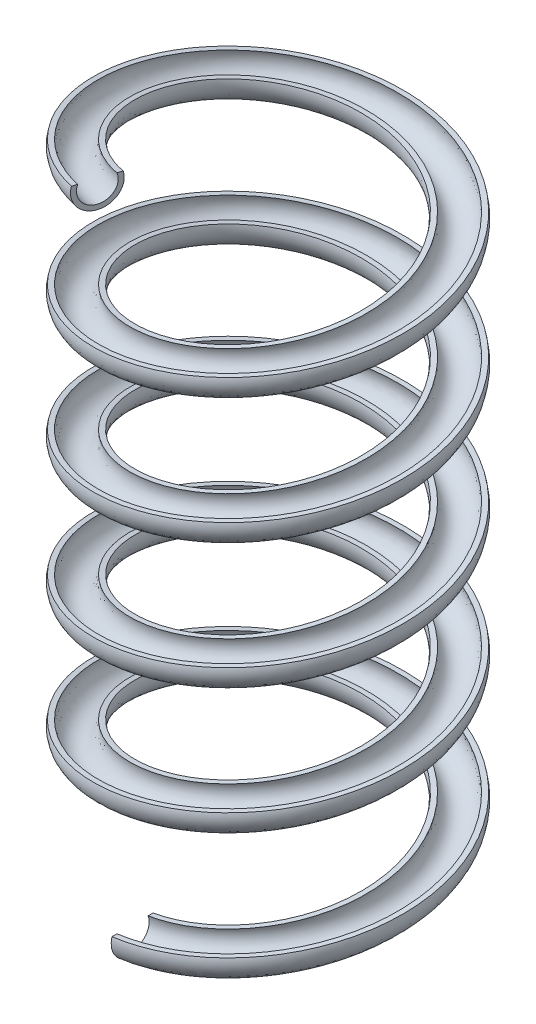
SolidWorks part; units mm, degrees
material "Custom Plastic"
ref_plane "Front Plane" through (0, 0, 0) normal (0, 0, 1) x (1, 0, 0)
ref_plane "Top Plane" through (0, 0, 0) normal (0, 1, 0) x (1, 0, 0)
ref_plane "Right Plane" through (0, 0, 0) normal (1, 0, 0) x (0, 0, -1)
sketch "Sketch2" plane through (0, 0, 0) normal (0, 1, 0) x (1, 0, 0)
  circle A0 centre (0, 0) radius 171.45
  dimension "D1" = 342.9
curve "Helix/Spiral2" pitch 159.0707 height 787.4 turns 4.95
ref_plane "Plane5" through (0, 0, 0) normal (1, 0, 0) x (0, 0, -1)
sketch "Sketch6" plane through (0, 0, 0) normal (1, 0, 0) x (0, 0, -1)
  line L0 (-151.765, 7.1842) -> (-145.415, 7.1842)
  line L1 (-191.135, 7.1842) -> (-197.485, 7.1842)
  arc A0 (-191.135, 7.1842) -> (-151.765, 7.1842) centre (-171.45, 0) ccw
  arc A1 (-145.415, 7.1842) -> (-197.485, 7.1842) centre (-171.45, 0) cw
  spline S0 degree 3 poles (-171.45, 0) (-171.45, 0.9078) (-170.7875, 2.7248) (-167.8175, 5.4491) (-162.9059, 8.1737) (-156.1093, 10.8983) (-147.5065, 13.6228) (-137.1969, 16.3474) (-125.2998, 19.072) (-111.953, 21.7965) (-97.3108, 24.5211) (-81.5427, 27.2457) (-64.831, 29.9702) (-47.3693, 32.6948) (-29.3594, 35.4194) (-11.0099, 38.1439) (7.4671, 40.8685) (25.8576, 43.5931) (43.949, 46.3176) (61.5318, 49.0422) (78.4027, 51.7668) (94.3665, 54.4913) (109.2383, 57.2159) (122.8462, 59.9405) (135.0327, 62.6651) (145.6568, 65.3896) (154.5955, 68.1142) (161.7455, 70.8388) (167.024, 73.5633) (170.37, 76.2879) (171.7446, 79.0125) (171.1321, 81.737) (168.5395, 84.4616) (163.9967, 87.1862) (157.5565, 89.9107) (149.2932, 92.6353) (139.3025, 95.3599) (127.7, 98.0844) (114.6199, 100.809) (100.2136, 103.5336) (84.6478, 106.2581) (68.1026, 108.9827) (50.7694, 111.7073) (32.8487, 114.4318) (14.548, 117.1564) (-3.9211, 119.881) (-22.3448, 122.6055) (-40.51, 125.3301) (-58.2064, 128.0547) (-75.2293, 130.7792) (-91.3819, 133.5038) (-106.477, 136.2284) (-120.3402, 138.9529) (-132.8109, 141.6775) (-143.745, 144.4021) (-153.0158, 147.1266) (-160.5162, 149.8512) (-166.1593, 152.5758) (-169.8798, 155.3003) (-171.6347, 158.0249) (-171.4037, 160.7495) (-169.1895, 163.474) (-165.0177, 166.1986) (-158.9365, 168.9232) (-151.0163, 171.6478) (-141.3487, 174.3723) (-130.0457, 177.0969) (-117.238, 179.8215) (-103.0737, 182.546) (-87.7169, 185.2706) (-71.3451, 187.9952) (-54.1478, 190.7197) (-36.3239, 193.4443) (-18.0798, 196.1689) (0.3735, 198.8934) (18.8225, 201.618) (37.0537, 204.3426) (54.8561, 207.0671) (72.0239, 209.7917) (88.3583, 212.5163) (103.6703, 215.2408) (117.7828, 217.9654) (130.5325, 220.69) (141.7719, 223.4145) (151.3708, 226.1391) (159.2184, 228.8637) (165.2236, 231.5882) (169.3172, 234.3128) (171.4516, 237.0374) (171.6023, 239.7619) (169.7674, 242.4865) (165.9682, 245.2111) (160.2486, 247.9356) (152.6749, 250.6602) (143.3347, 253.3848) (132.3359, 256.1093) (119.806, 258.8339) (105.8899, 261.5585) (90.7485, 264.283) (74.5571, 267.0076) (57.5031, 269.7322) (39.7837, 272.4567) (21.604, 275.1813) (3.1743, 277.9059) (-15.2921, 280.6304) (-33.5815, 283.355) (-51.4824, 286.0796) (-68.7877, 288.8042) (-85.297, 291.5287) (-100.8194, 294.2533) (-115.1752, 296.9779) (-128.1984, 299.7024) (-139.7383, 302.427) (-149.6613, 305.1516) (-157.8526, 307.8761) (-164.2175, 310.6007) (-168.6823, 313.3253) (-171.1954, 316.0498) (-171.7276, 318.7744) (-170.2728, 321.499) (-166.8479, 324.2235) (-161.4924, 326.9481) (-154.2684, 329.6727) (-145.2594, 332.3972) (-134.5697, 335.1218) (-122.3229, 337.8464) (-108.6608, 340.5709) (-93.7414, 343.2955) (-77.7374, 346.0201) (-60.8339, 348.7446) (-43.2265, 351.4692) (-25.119, 354.1938) (-6.7208, 356.9183) (11.7552, 359.6429) (30.0951, 362.3675) (48.0868, 365.092) (65.5221, 367.8166) (82.1993, 370.5412) (97.9254, 373.2657) (112.5185, 375.9903) (125.8096, 378.7149) (137.6451, 381.4394) (147.8879, 384.164) (156.4195, 386.8886) (163.1413, 389.6131) (167.9755, 392.3377) (170.8661, 395.0623) (171.7796, 397.7869) (170.7056, 400.5114) (167.6564, 403.236) (162.6674, 405.9606) (155.7961, 408.6851) (147.1223, 411.4097) (136.7461, 414.1343) (124.7877, 416.8588) (111.3854, 419.5834) (96.6944, 422.308) (80.8845, 425.0325) (64.1387, 427.7571) (46.6508, 430.4817) (28.6232, 433.2062) (10.2644, 435.9308) (-8.2132, 438.6554) (-26.5958, 441.3799) (-44.6707, 444.1045) (-62.2286, 446.8291) (-79.0666, 449.5536) (-94.9897, 452.2782) (-109.8137, 455.0028) (-123.3671, 457.7273) (-135.4931, 460.4519) (-146.0514, 463.1765) (-154.9197, 465.901) (-161.9956, 468.6256) (-167.197, 471.3502) (-170.4639, 474.0747) (-171.7584, 476.7993) (-171.0656, 479.5239) (-168.3935, 482.2484) (-163.7729, 484.973) (-157.2574, 487.6976) (-148.9223, 490.4221) (-138.8641, 493.1467) (-127.1992, 495.8713) (-114.0625, 498.5958) (-99.606, 501.3204) (-83.9971, 504.045) (-67.4162, 506.7696) (-50.0553, 509.4941) (-32.1152, 512.2187) (-13.8036, 514.9433) (4.6678, 517.6678) (23.0852, 520.3924) (41.2355, 523.117) (58.9086, 525.8415) (75.9001, 528.5661) (92.0135, 531.2907) (107.0622, 534.0152) (120.8721, 536.7398) (133.2834, 539.4644) (144.1526, 542.1889) (153.3538, 544.9135) (160.7807, 547.6381) (166.3472, 550.3626) (169.989, 553.0872) (171.664, 555.8118) (171.3526, 558.5363) (169.0586, 561.2609) (164.8086, 563.9855) (158.6515, 566.71) (150.6588, 569.4346) (140.9229, 572.1592) (129.5564, 574.8837) (116.6909, 577.6083) (102.4752, 580.3329) (87.0738, 583.0574) (70.6649, 585.782) (53.4384, 588.5066) (35.5936, 591.2311) (17.3369, 593.9557) (-1.1204, 596.6803) (-19.5647, 599.4048) (-37.7827, 602.1294) (-55.5634, 604.854) (-72.7013, 607.5785) (-88.998, 610.3031) (-104.2649, 613.0277) (-118.3254, 615.7522) (-131.0168, 618.4768) (-142.1923, 621.2014) (-151.7225, 623.926) (-159.4972, 626.6505) (-165.4265, 629.3751) (-169.4416, 632.0997) (-171.4962, 634.8242) (-171.5665, 637.5488) (-169.6517, 640.2734) (-165.7739, 642.9979) (-159.978, 645.7225) (-152.3311, 648.4471) (-142.9216, 651.1716) (-131.8584, 653.8962) (-119.2696, 656.6208) (-105.3007, 659.3453) (-90.1134, 662.0699) (-73.8835, 664.7945) (-56.7987, 667.519) (-39.0567, 670.2436) (-20.8628, 672.9682) (-2.4275, 675.6927) (16.0359, 678.4173) (34.3138, 681.1419) (52.1946, 683.8664) (69.4715, 686.591) (85.9445, 689.3156) (101.4232, 692.0401) (115.7283, 694.7647) (128.6944, 697.4893) (140.1714, 700.2138) (150.0265, 702.9384) (158.1458, 705.663) (164.4352, 708.3875) (168.822, 711.1121) (171.2554, 713.8367) (171.7073, 716.5612) (170.1724, 719.2858) (166.6686, 722.0104) (161.2363, 724.7349) (153.9384, 727.4595) (144.8593, 730.1841) (134.1042, 732.9087) (121.7974, 735.6332) (108.0813, 738.3578) (93.1146, 741.0824) (77.0706, 743.8069) (60.1348, 746.5315) (42.5032, 749.2561) (24.3798, 751.9806) (5.9743, 754.7052) (-12.5002, 757.4298) (-30.8302, 760.1543) (-48.8034, 762.8789) (-66.212, 765.6035) (-82.8544, 768.328) (-98.5382, 771.0526) (-113.0818, 773.7772) (-126.317, 776.5017) (-138.0906, 779.2263) (-148.2666, 781.9509) (-156.7264, 784.6752) (-161.159, 786.4922) (-163.0586, 787.4) knots 0 0 0 0 0.00346 0.00692 0.010381 0.013841 0.017301 0.020761 0.024221 0.027682 0.031142 0.034602 0.038062 0.041522 0.044983 0.048443 0.051903 0.055363 0.058824 0.062284 0.065744 0.069204 0.072664 0.076125 0.079585 0.083045 0.086505 0.089965 0.093426 0.096886 0.100346 0.103806 0.107266 0.110727 0.114187 0.117647 0.121107 0.124567 0.128028 0.131488 0.134948 0.138408 0.141869 0.145329 0.148789 0.152249 0.155709 0.15917 0.16263 0.16609 0.16955 0.17301 0.176471 0.179931 0.183391 0.186851 0.190311 0.193772 0.197232 0.200692 0.204152 0.207612 0.211073 0.214533 0.217993 0.221453 0.224913 0.228374 0.231834 0.235294 0.238754 0.242215 0.245675 0.249135 0.252595 0.256055 0.259516 0.262976 0.266436 0.269896 0.273356 0.276817 0.280277 0.283737 0.287197 0.290657 0.294118 0.297578 0.301038 0.304498 0.307958 0.311419 0.314879 0.318339 0.321799 0.32526 0.32872 0.33218 0.33564 0.3391 0.342561 0.346021 0.349481 0.352941 0.356401 0.359862 0.363322 0.366782 0.370242 0.373702 0.377163 0.380623 0.384083 0.387543 0.391003 0.394464 0.397924 0.401384 0.404844 0.408304 0.411765 0.415225 0.418685 0.422145 0.425606 0.429066 0.432526 0.435986 0.439446 0.442907 0.446367 0.449827 0.453287 0.456747 0.460208 0.463668 0.467128 0.470588 0.474048 0.477509 0.480969 0.484429 0.487889 0.491349 0.49481 0.49827 0.50173 0.50519 0.508651 0.512111 0.515571 0.519031 0.522491 0.525952 0.529412 0.532872 0.536332 0.539792 0.543253 0.546713 0.550173 0.553633 0.557093 0.560554 0.564014 0.567474 0.570934 0.574394 0.577855 0.581315 0.584775 0.588235 0.591696 0.595156 0.598616 0.602076 0.605536 0.608997 0.612457 0.615917 0.619377 0.622837 0.626298 0.629758 0.633218 0.636678 0.640138 0.643599 0.647059 0.650519 0.653979 0.657439 0.6609 0.66436 0.66782 0.67128 0.67474 0.678201 0.681661 0.685121 0.688581 0.692042 0.695502 0.698962 0.702422 0.705882 0.709343 0.712803 0.716263 0.719723 0.723183 0.726644 0.730104 0.733564 0.737024 0.740484 0.743945 0.747405 0.750865 0.754325 0.757785 0.761246 0.764706 0.768166 0.771626 0.775087 0.778547 0.782007 0.785467 0.788927 0.792388 0.795848 0.799308 0.802768 0.806228 0.809689 0.813149 0.816609 0.820069 0.823529 0.82699 0.83045 0.83391 0.83737 0.84083 0.844291 0.847751 0.851211 0.854671 0.858131 0.861592 0.865052 0.868512 0.871972 0.875433 0.878893 0.882353 0.885813 0.889273 0.892734 0.896194 0.899654 0.903114 0.906574 0.910035 0.913495 0.916955 0.920415 0.923875 0.927336 0.930796 0.934256 0.937716 0.941176 0.944637 0.948097 0.951557 0.955017 0.958478 0.961938 0.965398 0.968858 0.972318 0.975779 0.979239 0.982699 0.986159 0.989619 0.99308 0.99654 1 1 1 1 construction
  dimension "D1" = 20.955
  dimension "D2" = 39.37
  dimension "D3" = 6.35
sweep "Sweep2" add profiles "Sketch6" path "Helix/Spiral2"
